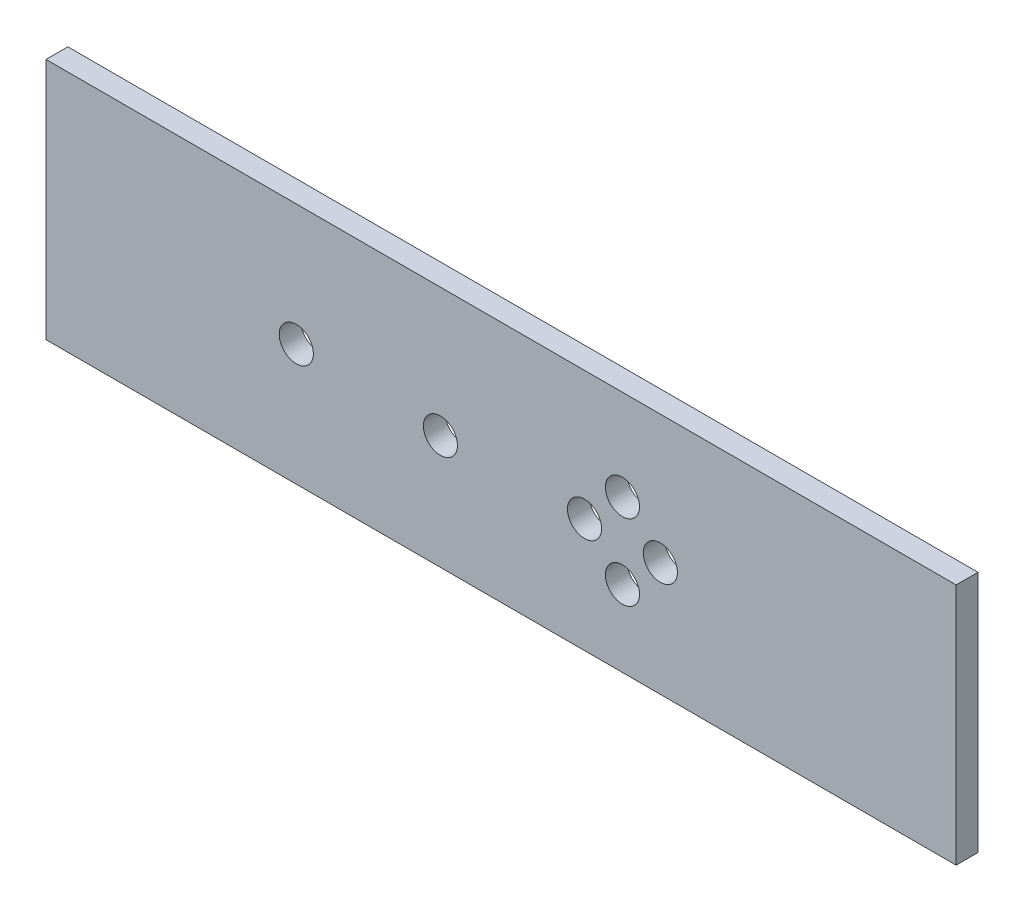
SolidWorks part; units mm, degrees
ref_plane "Front Plane" through (0, 0, 0) normal (0, 0, 1) x (1, 0, 0)
ref_plane "Top Plane" through (0, 0, 0) normal (0, 1, 0) x (1, 0, 0)
ref_plane "Right Plane" through (0, 0, 0) normal (1, 0, 0) x (0, 0, -1)
sketch "Sketch1" plane through (0, 0, 0) normal (0, 0, 1) x (1, 0, 0)
  line L1 (-322.4431, 234.2275) -> (439.5569, 234.2275)
  line L2 (-322.4431, 234.2275) -> (-322.4431, 31.0275)
  line L3 (-322.4431, 31.0275) -> (439.5569, 31.0275)
  line L4 (439.5569, 234.2275) -> (439.5569, 31.0275)
  dimension "D1" = 762
  dimension "D2" = 203.2
extrude "Boss-Extrude1" add sketch "Sketch1" along normal blind 18.288
sketch "Sketch2" plane through (0, 0, 0) normal (0, 0, -1) x (-1, 0, 0)
  line L0 (322.4431, 234.2275) -> (322.4431, 31.0275) construction
  circle A0 centre (112.8931, 132.6275) radius 14.2875
  dimension "D1" = 28.575
  dimension "D2" = 209.55
extrude "Cut-Extrude1" cut sketch "Sketch2" against normal through all
sketch "Sketch3" plane through (0, 0, 0) normal (0, 0, -1) x (-1, 0, 0)
  line L0 (-439.5569, 31.0275) -> (-439.5569, 234.2275) construction
  line L1 (-191.9069, 158.3266) -> (-128.4069, 158.3266) construction
  line L2 (-191.9069, 158.3266) -> (-191.9069, 94.8266) construction
  line L3 (-191.9069, 94.8266) -> (-128.4069, 94.8266) construction
  line L4 (-128.4069, 158.3266) -> (-128.4069, 94.8266) construction
  line L5 (-191.9069, 158.3266) -> (-128.4069, 94.8266) construction
  line L6 (-191.9069, 94.8266) -> (-128.4069, 158.3266) construction
  circle A0 centre (-128.4069, 126.5766) radius 14.2875
  circle A1 centre (-191.9069, 126.5766) radius 14.2875
  circle A2 centre (-160.1569, 158.3266) radius 14.2875
  circle A3 centre (-160.1569, 94.8266) radius 14.2875
  circle A4 centre (-7.7569, 126.5766) radius 14.2875
  point P4 (-160.1569, 126.5766)
  point P9 (-128.4069, 126.5766)
  point P10 (-191.9069, 126.5766)
  dimension "D1" = 28.575
  dimension "D2" = 28.575
  dimension "D8" = 28.575
  dimension "D9" = 28.575
  dimension "D11" = 28.575
  dimension "D12" = 431.8
  dimension "D3" = 63.5
  dimension "D4" = 0
  dimension "D5" = 63.5
  dimension "D6" = 0
  dimension "D7" = 0
  dimension "D10" = 279.4
extrude "Cut-Extrude2" cut sketch "Sketch3" against normal through all
